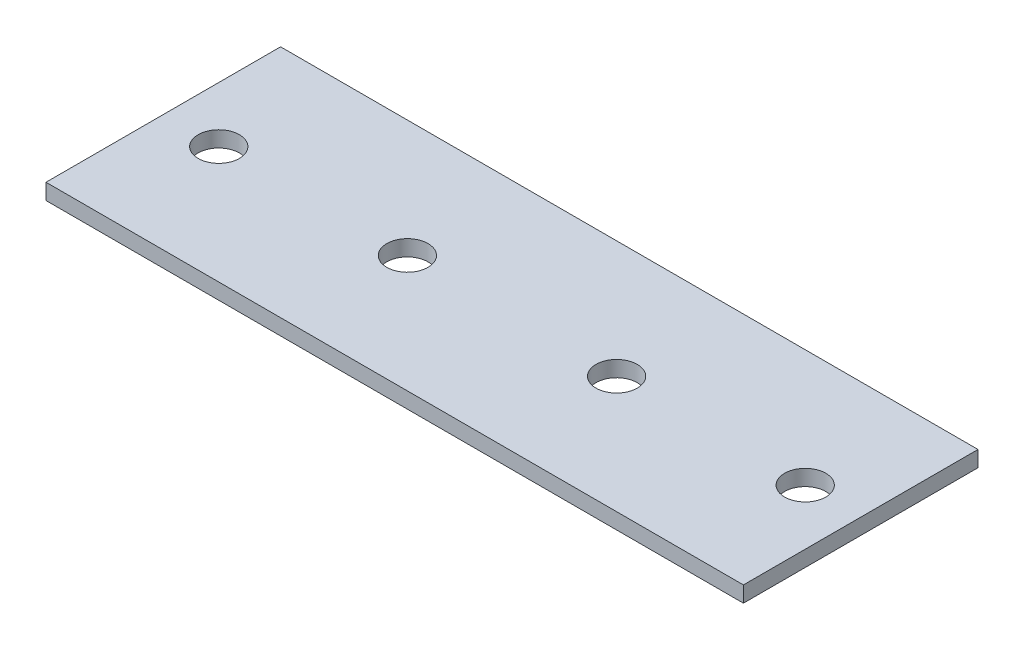
SolidWorks part; units mm, degrees
material "1.0553 (S355J0)"
ref_plane "Płaszczyzna przednia" through (0, 0, 0) normal (0, 0, 1) x (1, 0, 0)
ref_plane "Płaszczyzna górna" through (0, 0, 0) normal (0, 1, 0) x (1, 0, 0)
ref_plane "Płaszczyzna prawa" through (0, 0, 0) normal (1, 0, 0) x (0, 0, -1)
sketch "Szkic1" plane through (0, 0, 0) normal (0, 1, 0) x (1, 0, 0)
  line L0 (0, 37) -> (220, 37) construction
  line L1 (0, 0) -> (220, 0)
  line L2 (0, 0) -> (0, 74)
  line L3 (0, 74) -> (220, 74)
  line L4 (220, 0) -> (220, 74)
  line L5 (110, 74) -> (110, 0) construction
  circle A0 centre (17.5, 37) radius 6.5
  circle A1 centre (77, 37) radius 6.5
  circle A2 centre (202.5, 37) radius 6.5
  circle A3 centre (143, 37) radius 6.5
  dimension "D4" = 13
  dimension "D5" = 13
  dimension "D1" = 220
  dimension "D2" = 74
  dimension "D3" = 92.5
  dimension "D6" = 33
extrude "Dodanie-wyciągnięcie1" add sketch "Szkic1" along normal blind 5
